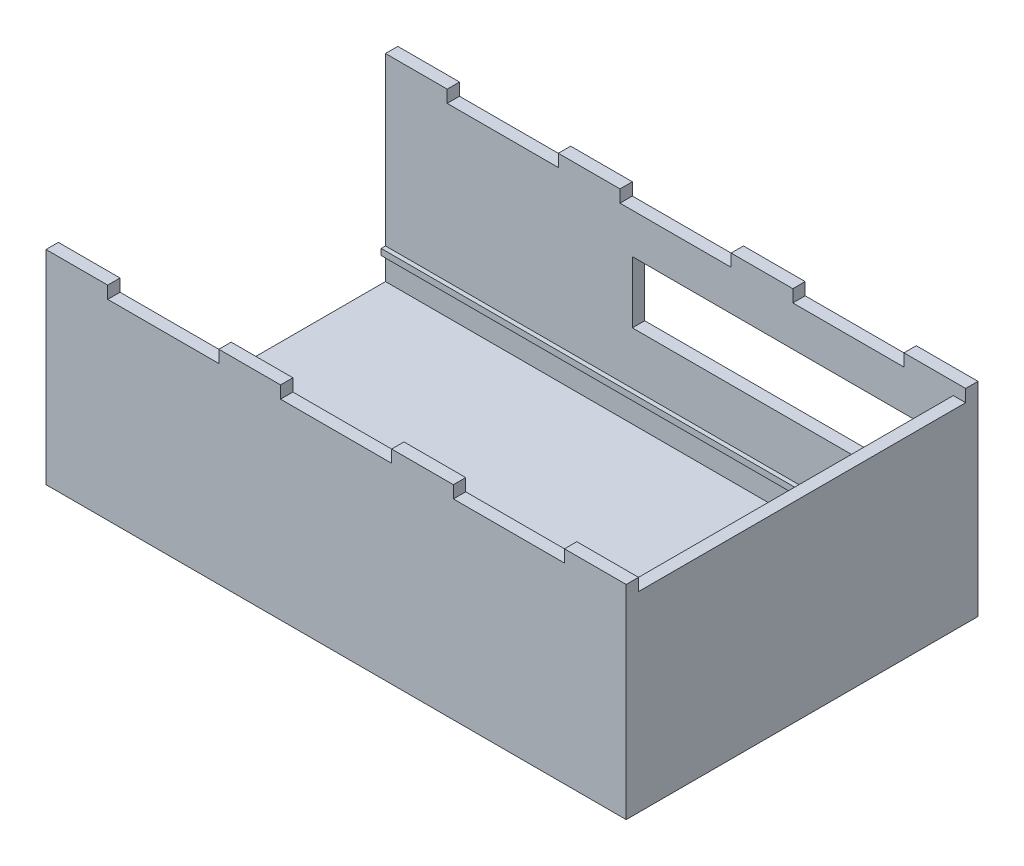
SolidWorks part; units mm, degrees
ref_plane "Front Plane" through (0, 0, 0) normal (0, 0, 1) x (1, 0, 0)
ref_plane "Top Plane" through (0, 0, 0) normal (0, 1, 0) x (1, 0, 0)
ref_plane "Right Plane" through (0, 0, 0) normal (1, 0, 0) x (0, 0, -1)
sketch "Sketch1" plane through (0, 0, 0) normal (0, 1, 0) x (1, 0, 0)
  line L0 (-56.4505, 24.5887) -> (-56.4505, -32.4113)
  line L1 (-53.9505, 22.0887) -> (35.0495, 22.0887) construction
  line L2 (-53.9505, 22.0887) -> (-53.9505, -29.9113) construction
  line L3 (-53.9505, -29.9113) -> (35.0495, -29.9113) construction
  line L4 (35.0495, 22.0887) -> (35.0495, -29.9113) construction
  line L5 (-56.4505, -32.4113) -> (37.5495, -32.4113)
  line L6 (37.5495, 24.5887) -> (37.5495, -32.4113)
  line L7 (-56.4505, 24.5887) -> (37.5495, 24.5887)
  dimension "D1" = 89
  dimension "D2" = 52
  dimension "D3" = 2.5
extrude "Boss-Extrude1" add sketch "Sketch1" along normal blind 1
sketch "Sketch2" plane through (0, 1, 0) normal (0, 1, 0) x (1, 0, 0)
  line L1 (-56.4505, 24.5887) -> (37.5495, 24.5887)
  line L2 (-56.4505, 24.5887) -> (-56.4505, 22.5887)
  line L3 (-56.4505, -32.4113) -> (37.5495, -32.4113)
  line L4 (37.5495, 24.5887) -> (37.5495, -32.4113)
  line L5 (-54.4505, -30.4113) -> (35.5495, -30.4113)
  line L6 (35.5495, 22.5887) -> (35.5495, -30.4113)
  line L7 (-54.4505, 22.5887) -> (35.5495, 22.5887)
  line L8 (-56.4505, 22.5887) -> (-54.4505, 22.5887)
  line L9 (-56.4505, -30.4113) -> (-54.4505, -30.4113)
  line L10 (-56.4505, -30.4113) -> (-56.4505, -32.4113)
  line L11 (-54.4505, 22.5887) -> (-54.4505, -30.4113) construction
  line L12 (-56.4505, 24.5887) -> (-56.4505, -32.4113) construction
  dimension "D1" = 2
extrude "Boss-Extrude3" add sketch "Sketch2" along normal blind 30
sketch "Sketch5" plane through (-56.4505, 0, 0) normal (-1, 0, 0) x (0, 0, 1)
  line L0 (-22.5887, 31) -> (-22.5887, 1) construction
  line L1 (-22.5887, 6) -> (-21.8887, 6)
  line L2 (-22.5887, 6) -> (-22.5887, 5)
  line L3 (-22.5887, 5) -> (-21.8887, 5)
  line L4 (-21.8887, 6) -> (-21.8887, 5)
  line L5 (30.4113, 31) -> (30.4113, 1) construction
  line L6 (30.4113, 6) -> (29.7113, 6)
  line L7 (30.4113, 6) -> (30.4113, 5)
  line L8 (30.4113, 5) -> (29.7113, 5)
  line L9 (29.7113, 6) -> (29.7113, 5)
  line L10 (-22.5887, 1) -> (30.4113, 1) construction
  line L11 (-22.5887, 1) -> (30.4113, 1) construction
  dimension "D1" = 1
  dimension "D2" = 1
  dimension "D3" = 0.7
  dimension "D4" = 0.7
  dimension "D5" = 4
  dimension "D6" = 4
extrude "Boss-Extrude4" add sketch "Sketch5" against normal up to surface (92 mm away) up to face at (35.5495, 16, 3.9113)
sketch "Sketch6" plane through (0, 0, -24.5887) normal (0, 0, -1) x (-1, 0, 0)
  line L0 (-37.5495, 31) -> (-37.5495, 0) construction
  line L1 (-30.5495, 24.5) -> (16.4505, 24.5)
  line L2 (-30.5495, 24.5) -> (-30.5495, 14.5)
  line L3 (-30.5495, 14.5) -> (16.4505, 14.5)
  line L4 (16.4505, 24.5) -> (16.4505, 14.5)
  point P4 (-30.5495, 19.5)
  dimension "D1" = 7
  dimension "D2" = 8.5
  dimension "D3" = 10
  dimension "D4" = 47
extrude "Cut-Extrude2" cut sketch "Sketch6" against normal blind 30
sketch "Sketch7" plane through (0, 31, 0) normal (0, 1, 0) x (1, 0, 0)
  line L0 (-56.4505, 22.5887) -> (35.5495, 22.5887) construction
  line L1 (-56.4505, 24.5887) -> (-46.4505, 24.5887)
  line L2 (-56.4505, 24.5887) -> (-56.4505, 22.5887)
  line L3 (-56.4505, 22.5887) -> (-46.4505, 22.5887)
  line L4 (-46.4505, 24.5887) -> (-46.4505, 22.5887)
  line L5 (37.5495, 24.5887) -> (-56.4505, 24.5887) construction
  line L6 (-28.4505, 24.5887) -> (-18.4505, 24.5887)
  line L7 (-28.4505, 24.5887) -> (-28.4505, 22.5887)
  line L8 (-28.4505, 22.5887) -> (-18.4505, 22.5887)
  line L9 (-18.4505, 24.5887) -> (-18.4505, 22.5887)
  line L10 (37.5495, -32.4113) -> (37.5495, 24.5887) construction
  line L11 (-0.4505, 24.5887) -> (9.5495, 24.5887)
  line L12 (-0.4505, 24.5887) -> (-0.4505, 22.5887)
  line L13 (-0.4505, 22.5887) -> (9.5495, 22.5887)
  line L14 (9.5495, 24.5887) -> (9.5495, 22.5887)
  line L15 (27.5495, 24.5887) -> (37.5495, 24.5887)
  line L16 (27.5495, 24.5887) -> (27.5495, 22.5887)
  line L17 (27.5495, 22.5887) -> (37.5495, 22.5887)
  line L18 (37.5495, 24.5887) -> (37.5495, 22.5887)
  line L19 (-56.4505, -32.4113) -> (37.5495, -32.4113) construction
  line L20 (-56.4505, -30.4113) -> (-46.4505, -30.4113)
  line L21 (-56.4505, -30.4113) -> (-56.4505, -32.4113)
  line L22 (-56.4505, -32.4113) -> (-46.4505, -32.4113)
  line L23 (-46.4505, -30.4113) -> (-46.4505, -32.4113)
  line L24 (35.5495, -30.4113) -> (-56.4505, -30.4113) construction
  line L25 (-28.4505, -32.4113) -> (-18.4505, -32.4113)
  line L26 (-28.4505, -32.4113) -> (-28.4505, -30.4113)
  line L27 (-28.4505, -30.4113) -> (-18.4505, -30.4113)
  line L28 (-18.4505, -32.4113) -> (-18.4505, -30.4113)
  line L30 (-0.4505, -30.4113) -> (9.5495, -30.4113)
  line L31 (-0.4505, -30.4113) -> (-0.4505, -32.4113)
  line L32 (-0.4505, -32.4113) -> (9.5495, -32.4113)
  line L33 (9.5495, -30.4113) -> (9.5495, -32.4113)
  line L34 (27.5495, -32.4113) -> (37.5495, -32.4113)
  line L35 (27.5495, -32.4113) -> (27.5495, -30.4113)
  line L36 (27.5495, -30.4113) -> (37.5495, -30.4113)
  line L37 (37.5495, -32.4113) -> (37.5495, -30.4113)
  dimension "D1" = 10
  dimension "D2" = 10
  dimension "D3" = 10
  dimension "D4" = 10
  dimension "D5" = 0
  dimension "D6" = 18
  dimension "D7" = 18
  dimension "D8" = 18
  dimension "D9" = 0
  dimension "D10" = 10
  dimension "D11" = 10
  dimension "D12" = 10
  dimension "D13" = 10
  dimension "D14" = 18
  dimension "D15" = 18
  dimension "D16" = 18
extrude "Boss-Extrude5" add sketch "Sketch7" along normal blind 2
